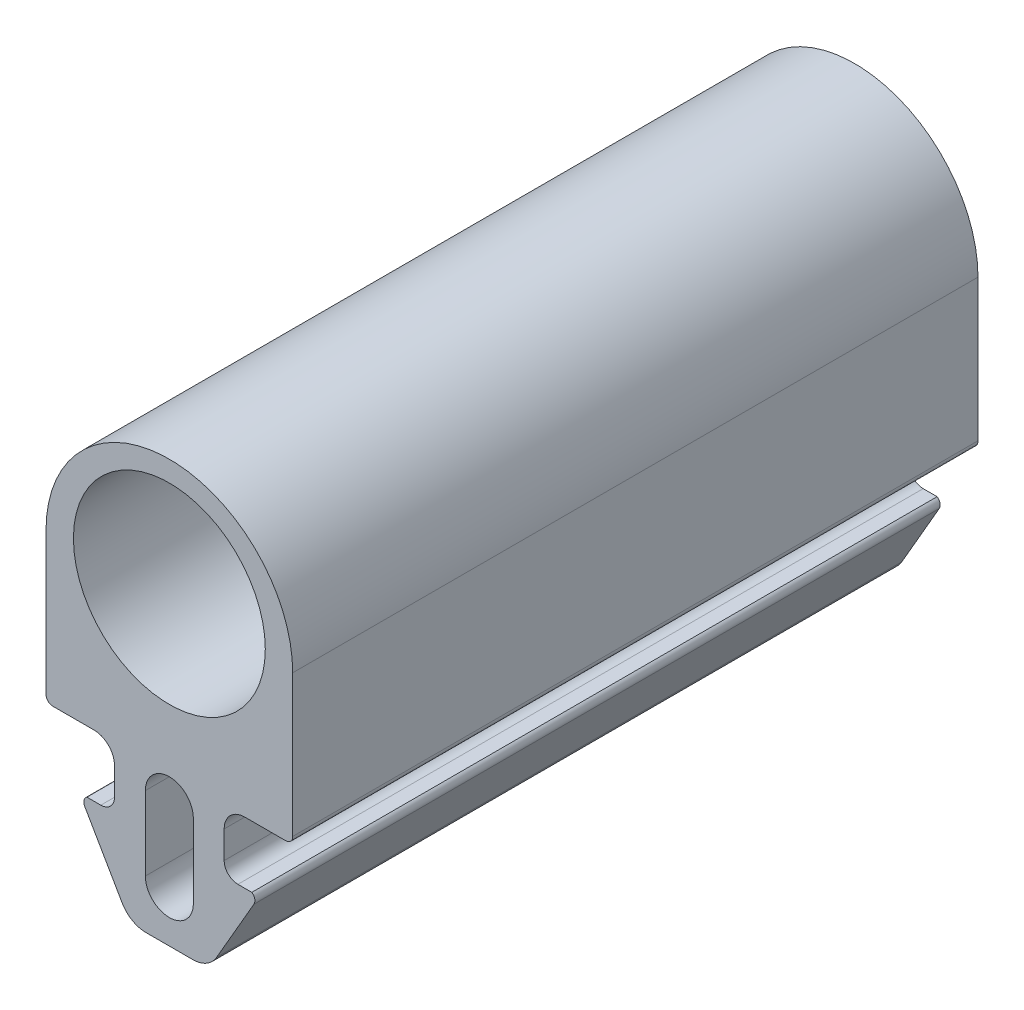
SolidWorks part; units mm, degrees
ref_plane "Plan de face" through (0, 0, 0) normal (0, 0, 1) x (1, 0, 0)
ref_plane "Plan de dessus" through (0, 0, 0) normal (0, 1, 0) x (1, 0, 0)
ref_plane "Plan de droite" through (0, 0, 0) normal (1, 0, 0) x (0, 0, -1)
ref_plane "Plan1" through (0, 0, 20) normal (0, 0, 1) x (1, 0, 0)
sketch "Esquisse1" plane through (0, 0, 20) normal (0, 0, 1) x (1, 0, 0)
  line L0 (-9, 10.8646) -> (-9, 0.5239)
  line L1 (-8.4781, 0) -> (-5.5, 0)
  line L2 (-4, -1.5) -> (-4, -3.5)
  line L3 (-5, -4.5) -> (-6.016, -4.5)
  line L4 (-6.1742, -5.1677) -> (-3.44, -9.9034)
  line L5 (-1.708, -10.9034) -> (1.708, -10.9034)
  line L6 (3.44, -9.9034) -> (6.1742, -5.1677)
  line L7 (6.016, -4.5) -> (5, -4.5)
  line L8 (4, -3.5) -> (4, -1.5)
  line L9 (5.5, 0) -> (8.4781, 0)
  line L10 (9, 0.5239) -> (9, 10.8646)
  line L11 (1.75, -1.9534) -> (1.75, -7.3515)
  line L12 (-1.75, -7.3515) -> (-1.75, -1.9534)
  arc A0 (9, 10.8646) -> (-9, 10.8646) centre (0, 10.8646) ccw
  arc A1 (-9, 0.5239) -> (-8.4781, 0) centre (-8.5006, 0.4995) ccw
  arc A2 (-5.5, 0) -> (-4, -1.5) centre (-5.5, -1.5) cw
  arc A3 (-4, -3.5) -> (-5, -4.5) centre (-5, -3.5) cw
  arc A4 (-6.016, -4.5) -> (-6.1742, -5.1677) centre (-5.7412, -4.9177) ccw
  arc A5 (-3.44, -9.9034) -> (-1.708, -10.9034) centre (-1.708, -8.9034) ccw
  arc A6 (1.708, -10.9034) -> (3.44, -9.9034) centre (1.708, -8.9034) ccw
  arc A7 (6.1742, -5.1677) -> (6.016, -4.5) centre (5.7412, -4.9177) ccw
  arc A8 (5, -4.5) -> (4, -3.5) centre (5, -3.5) cw
  arc A9 (4, -1.5) -> (5.5, 0) centre (5.5, -1.5) cw
  arc A10 (8.4781, 0) -> (9, 0.5239) centre (8.5006, 0.4995) ccw
  arc A11 (-1.75, -1.9534) -> (1.75, -1.9534) centre (0, -1.9534) cw
  arc A12 (1.75, -7.3515) -> (-1.75, -7.3515) centre (0, -7.3515) cw
  circle A13 centre (0, 11.36) radius 7
extrude "Boss.-Extru.1" add sketch "Esquisse1" against normal blind 50
